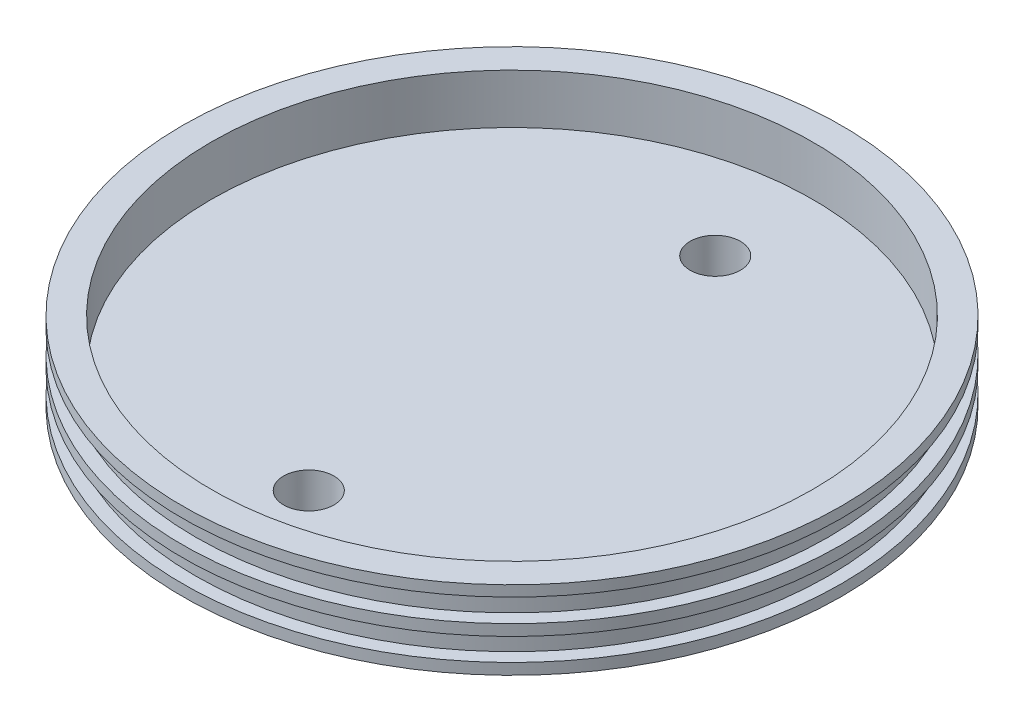
SolidWorks part; units mm, degrees
material "6061-T6 (SS)"
ref_plane "Front Plane" through (0, 0, 0) normal (0, 0, 1) x (1, 0, 0)
ref_plane "Top Plane" through (0, 0, 0) normal (0, 1, 0) x (1, 0, 0)
ref_plane "Right Plane" through (0, 0, 0) normal (1, 0, 0) x (0, 0, -1)
sketch "Sketch1" plane through (0, 0, 0) normal (0, 0, 1) x (1, 0, 0)
  line L0 (0, 48.1922) -> (0, -25.6743) construction
  line L1 (0, 0) -> (72.898, 0)
  line L2 (72.898, 0) -> (72.898, 2.4638)
  line L3 (72.898, 2.4638) -> (69.977, 2.4638)
  line L4 (69.977, 2.4638) -> (69.977, 7.4422)
  line L5 (69.977, 7.4422) -> (72.898, 7.4422)
  line L6 (72.898, 7.4422) -> (72.898, 9.906)
  line L7 (72.898, 9.906) -> (69.977, 9.906)
  line L8 (66.548, 17.3482) -> (66.548, 6.35)
  line L9 (66.548, 6.35) -> (0, 6.35)
  line L10 (0, 6.35) -> (0, 0)
  line L11 (69.977, 9.906) -> (69.977, 14.986)
  line L12 (69.977, 14.986) -> (72.898, 14.986)
  line L13 (72.898, 14.986) -> (72.898, 17.3482)
  line L14 (72.898, 17.3482) -> (66.548, 17.3482)
  dimension "D1" = 145.796
  dimension "D2" = 4.9784
  dimension "D3" = 2.921
  dimension "D4" = 9.906
  dimension "D5" = 6.35
  dimension "D6" = 6.35
  dimension "D7" = 5.08
  dimension "D8" = 9.906
revolve "Revolve1" add sketch "Sketch1" angle 360 about L0
sketch "Sketch6" plane through (0, 0, 0) normal (0, -1, 0) x (1, 0, 0)
  circle A0 centre (0, 0) radius 66.04
  dimension "D1" = 132.08
extrude "Boss-Extrude1" add sketch "Sketch6" along normal blind 2.54
fillet "CNC ID Fillet" [suppressed] radius 0.1778
fillet "CNC OD Fillet" [suppressed] radius 0.127
chamfer "CNC Chamfers" [suppressed] distance 0.254 angle 45
fillet "CNC Bore Fillet" [suppressed] radius 0.254
hole_wizard "Pipe Tap Drill for 1/4 Tap - Relief Valve" positions "Sketch13" profile "Sketch14" hole size "1/4" standard "ANSI Inch" end condition through all
sketch "Sketch13" plane through (0, -2.54, 0) normal (0, -1, 0) x (-1, 0, 0)
  point P4 (0, 44.958)
  point P5 (0, 55.7869)
  point P7 (0, 0)
  dimension "D1" = 44.958
sketch "Sketch14" plane through (0, -2.54, -44.958) normal (1, 0, 0) x (0, 0, -1)
  line L0 (0, 0) -> (0, 19.8882)
  line L1 (0, 19.8882) -> (5.5626, 19.8882)
  line L2 (5.5626, 19.8882) -> (5.5626, 0)
  line L5 (5.5626, 0) -> (0, 0)
  line L11 (0, -6.35) -> (0, 107.95) construction
  dimension "Thru Hole Dia." = 11.1252
  dimension "Thru Hole Depth" = 19.8882
hole_wizard "Pipe Tap Drill for 1/4 Tap - Vent Valve" positions "Sketch15" profile "Sketch16" hole size "1/4" standard "ANSI Inch" end condition through all
sketch "Sketch15" plane through (0, -2.54, 0) normal (0, -1, 0) x (-1, 0, 0)
  point P4 (0, -44.958)
  point P5 (-47.488, -26.0954)
  point P6 (0, 0)
  point P7 (0, -49.8855)
  point P11 (0, -44.958)
  point P12 (0, 0)
  dimension "D1" = 44.958
sketch "Sketch16" plane through (0, -2.54, 44.958) normal (1, 0, 0) x (0, 0, -1)
  line L0 (0, 0) -> (0, 19.8882)
  line L1 (0, 19.8882) -> (5.5626, 19.8882)
  line L2 (5.5626, 19.8882) -> (5.5626, 0)
  line L5 (5.5626, 0) -> (0, 0)
  line L11 (0, -6.35) -> (0, 107.95) construction
  dimension "Thru Hole Dia." = 11.1252
  dimension "Thru Hole Depth" = 19.8882
